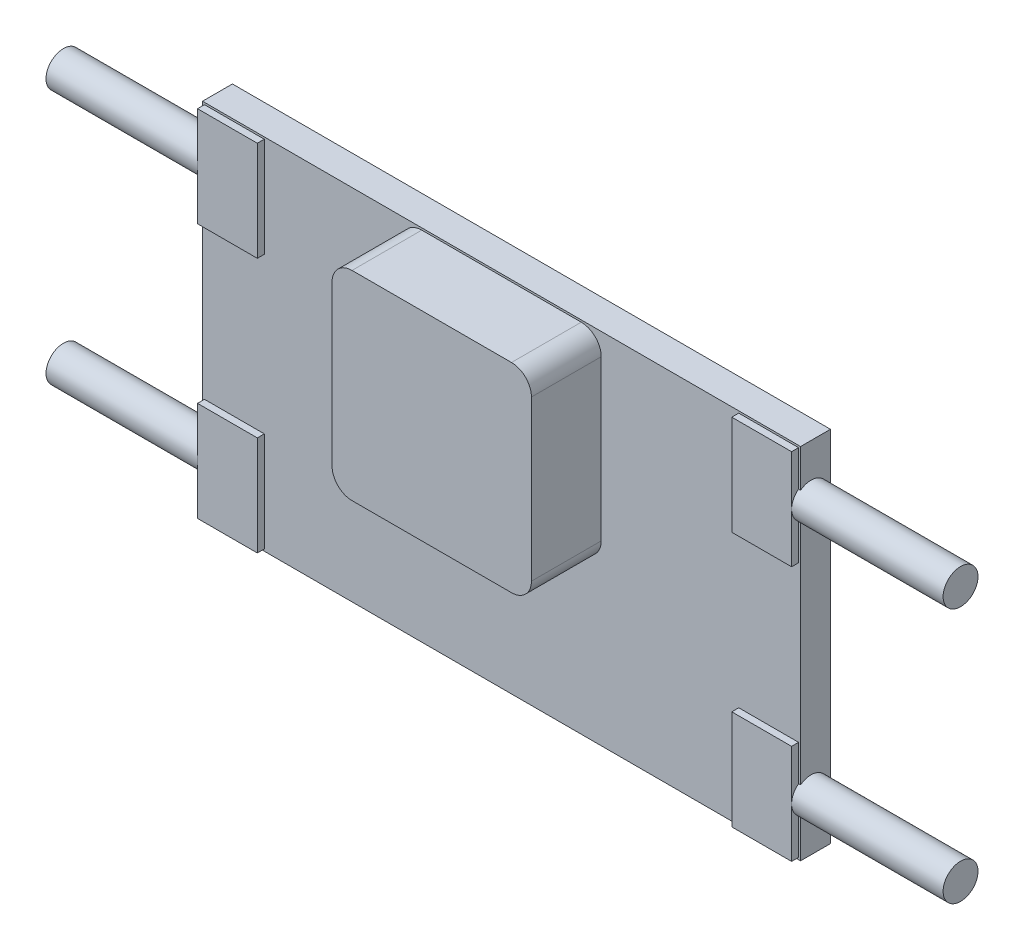
SolidWorks part; units mm, degrees
ref_plane "Front Plane" through (0, 0, 0) normal (0, 0, 1) x (1, 0, 0)
ref_plane "Top Plane" through (0, 0, 0) normal (0, 1, 0) x (1, 0, 0)
ref_plane "Right Plane" through (0, 0, 0) normal (1, 0, 0) x (0, 0, -1)
sketch "Sketch1" plane through (0, 0, 0) normal (0, 0, 1) x (1, 0, 0)
  line L1 (-15, -9) -> (15, -9)
  line L2 (-15, -9) -> (-15, 9)
  line L3 (-15, 9) -> (15, 9)
  line L4 (15, -9) -> (15, 9)
  dimension "D1" = 30
  dimension "D2" = 15
  dimension "D3" = 18
  dimension "D4" = 9
extrude "Boss-Extrude1" add sketch "Sketch1" along normal blind 1.5
sketch "Sketch2" plane through (0, 0, 1.5) normal (0, 0, 1) x (1, 0, 0)
  line L0 (15, 9) -> (-15, 9) construction
  line L1 (-4, -1.1) -> (4, -1.1)
  line L2 (-5, -0.1) -> (-5, 7.9)
  line L3 (-4, 8.9) -> (4, 8.9)
  line L4 (5, -0.1) -> (5, 7.9)
  arc A0 (4, -1.1) -> (5, -0.1) centre (4, -0.1) ccw
  arc A1 (4, 8.9) -> (5, 7.9) centre (4, 7.9) cw
  arc A2 (-5, 7.9) -> (-4, 8.9) centre (-4, 7.9) cw
  arc A3 (-4, -1.1) -> (-5, -0.1) centre (-4, -0.1) cw
  point P11 (5, 8.9)
  point P14 (-5, 8.9)
  point P17 (-5, -1.1)
  dimension "D5" = 1
  dimension "D1" = 0.1
  dimension "D2" = 10
  dimension "D3" = 10
  dimension "D4" = 5
extrude "Boss-Extrude2" add sketch "Sketch2" along normal blind 3.5
sketch "Sketch3" plane through (0, 0, 1.5) normal (0, 0, 1) x (1, 0, 0)
  line L1 (-14.9, 3.9) -> (-11.9, 3.9)
  line L2 (-14.9, 3.9) -> (-14.9, 8.9)
  line L3 (-14.9, 8.9) -> (-11.9, 8.9)
  line L4 (-11.9, 3.9) -> (-11.9, 8.9)
  line L5 (0, -1000) -> (0, 49000) construction
  line L6 (-14.9, -8.9) -> (-11.9, -8.9)
  line L7 (-14.9, -8.9) -> (-14.9, -3.9)
  line L8 (-14.9, -3.9) -> (-11.9, -3.9)
  line L9 (-11.9, -8.9) -> (-11.9, -3.9)
  line L12 (-15, 9) -> (-15, -9) construction
  line L13 (-15, -9) -> (15, -9) construction
  line L14 (15, 9) -> (-15, 9) construction
  point P11 (0, 0)
  point P14 (0, 0)
  point P17 (0, 0)
  point P18 (0, 0)
  dimension "D1" = 3
  dimension "D2" = 5
  dimension "D3" = 5
  dimension "D4" = 3
  dimension "D5" = 0.1
  dimension "D6" = 0.1
  dimension "D7" = 0.1
  dimension "D8" = 0.1
extrude "Boss-Extrude3" add sketch "Sketch3" along normal blind 0.35
sketch "Sketch4" plane through (-15, 0, 0) normal (-1, 0, 0) x (0, 0, 1)
  line L0 (1.85, 3.9) -> (1.5, 3.9) construction
  line L1 (-1000, 0) -> (49000, 0) construction
  line L2 (0, 9) -> (0, -9) construction
  line L3 (1.85, 8.9) -> (1.85, 3.9) construction
  circle A0 centre (0.975, 6.4) radius 0.875
  circle A1 centre (0.975, -6.4) radius 0.875
  point P9 (0, 0)
  dimension "D1" = 1.75
  dimension "D2" = 2.5
extrude "Boss-Extrude4" add sketch "Sketch4" along normal blind 7.5 and the other way up to surface other way up to face at (-14.9, -6.4, 1.675)
mirror "Mirror2" about plane through (0, 0, 0) normal (1, 0, 0) of "Boss-Extrude4", "Boss-Extrude3"
